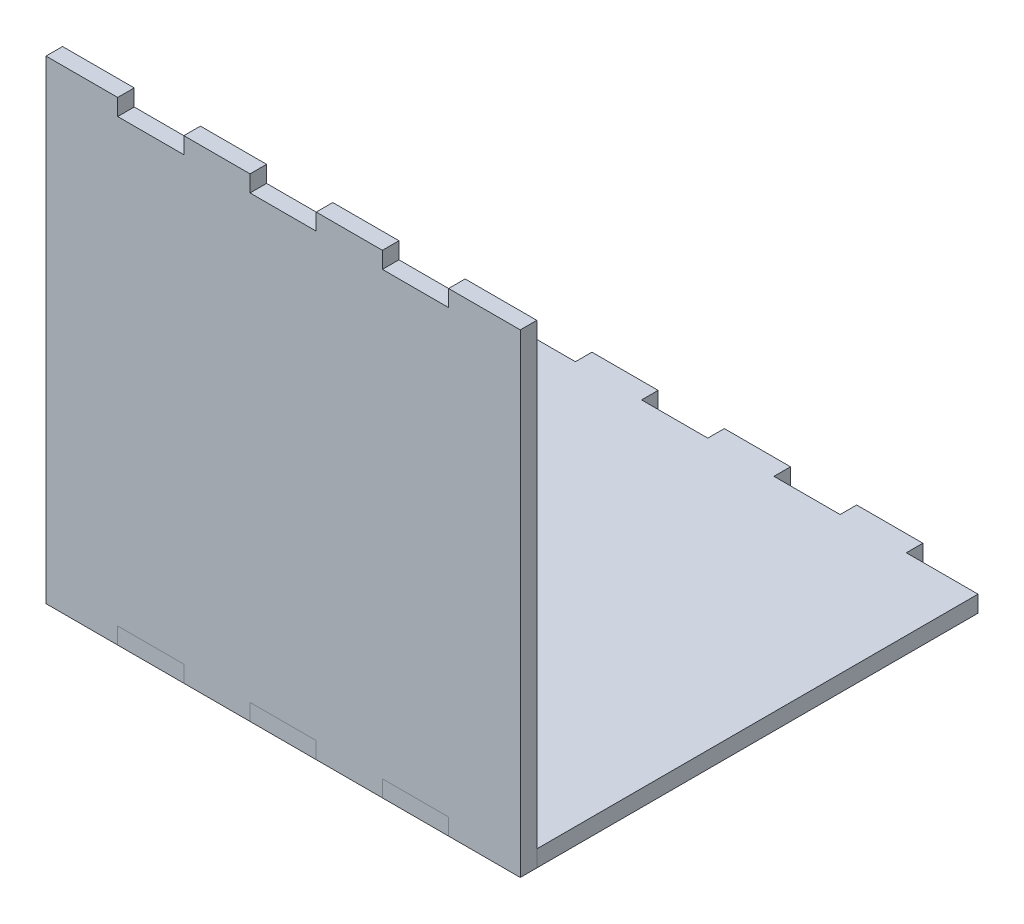
SolidWorks part; units mm, degrees
ref_plane "Alzado" through (0, 0, 0) normal (0, 0, 1) x (1, 0, 0)
ref_plane "Planta" through (0, 0, 0) normal (0, 1, 0) x (1, 0, 0)
ref_plane "Vista lateral" through (0, 0, 0) normal (1, 0, 0) x (0, 0, -1)
sketch "Croquis1" plane through (0, 0, 0) normal (0, 0, 1) x (1, 0, 0)
  line L0 (-3, -3) -> (83, 83) construction
  line L1 (10, 0) -> (22, 0)
  line L2 (0, 0) -> (0, 40) construction
  line L3 (10, 80) -> (22, 80)
  line L4 (80, 0) -> (80, 40) construction
  line L5 (10, 83) -> (10, 80)
  line L6 (-3, -3) -> (-3, 83)
  line L7 (-3, 83) -> (10, 83)
  line L8 (83, -3) -> (83, 83)
  line L9 (-3, -3) -> (10, -3)
  line L10 (-3, 83) -> (83, -3) construction
  line L11 (22, 83) -> (22, 80)
  line L12 (34, 83) -> (34, 80)
  line L13 (46, 83) -> (46, 80)
  line L14 (58, 83) -> (58, 80)
  line L15 (70, 83) -> (70, 80)
  line L16 (10, 83) -> (22, 83) construction
  line L17 (40, 40) -> (111.949, 40) construction
  line L18 (111.949, 40) -> (40, 40) construction
  line L19 (40, 40) -> (-8.8187, 40) construction
  line L20 (70, -3) -> (70, 0)
  line L21 (58, -3) -> (58, 0)
  line L22 (46, -3) -> (46, 0)
  line L23 (22, -3) -> (22, 0)
  line L24 (34, -3) -> (34, 0)
  line L25 (10, -3) -> (10, 0)
  line L26 (22, 83) -> (34, 83)
  line L27 (-3, 83) -> (83, 83) construction
  line L28 (46, 83) -> (58, 83)
  line L29 (70, 83) -> (83, 83)
  line L30 (0, 0) -> (10, 0) construction
  line L31 (0, 0) -> (80, 0) construction
  line L32 (22, 0) -> (34, 0) construction
  line L33 (34, 0) -> (46, 0)
  line L34 (46, 0) -> (58, 0) construction
  line L35 (58, 0) -> (70, 0)
  line L36 (70, 0) -> (80, 0) construction
  line L37 (58, -3) -> (70, -3) construction
  line L38 (70, -3) -> (83, -3)
  line L39 (-3, -3) -> (83, -3) construction
  line L40 (34, -3) -> (46, -3) construction
  line L41 (46, -3) -> (58, -3)
  line L42 (10, -3) -> (22, -3) construction
  line L43 (22, -3) -> (34, -3)
  line L44 (0, 80) -> (10, 80) construction
  line L45 (0, 80) -> (80, 80) construction
  line L46 (22, 80) -> (34, 80) construction
  line L47 (34, 80) -> (46, 80)
  line L48 (46, 80) -> (58, 80) construction
  line L49 (58, 80) -> (70, 80)
  line L50 (70, 80) -> (80, 80) construction
  line L51 (0, 40) -> (0, 80) construction
  line L52 (0, 0) -> (0, 80) construction
  line L53 (80, 40) -> (80, 80) construction
  line L54 (80, 0) -> (80, 80) construction
  point P12 (0, 0)
  point P26 (0, 0)
  dimension "D1" = 80
  dimension "D2" = 80
  dimension "D5" = 12
  dimension "D6" = 10
  dimension "D3" = 3
  dimension "D4" = 6
extrude "Saliente-Extruir1" add sketch "Croquis1" along normal blind 3 contours L14 L49 L15 L29 L8 L38 L20 L35 L21 L41 L22 L33 L24 L43 L23 L1 L25 L9 L6 L7 L5 L3 L11 L26 L12 L47 L13 L28
sketch "Croquis4" plane through (0, 0, 0) normal (0, 1, 0) x (1, 0, 0)
  line L0 (-3, 0) -> (-3, 80)
  line L1 (0, 0) -> (10, 0)
  line L3 (0, 80) -> (10, 80)
  line L4 (80, 0) -> (80, 40) construction
  line L5 (10, 83) -> (22, 83)
  line L6 (83, 0) -> (83, 80)
  line L7 (10, -3) -> (22, -3)
  line L8 (-3, 0) -> (0, 0)
  line L9 (83, 0) -> (80, 0)
  line L10 (0, 80) -> (-3, 80)
  line L11 (80, 80) -> (83, 80)
  line L12 (10, 0) -> (10, -3)
  line L13 (22, 0) -> (22, -3)
  line L14 (34, 0) -> (34, -3)
  line L15 (46, 0) -> (46, -3)
  line L16 (58, 0) -> (58, -3)
  line L17 (70, 0) -> (70, -3)
  line L18 (0, 40) -> (80, 40) construction
  line L19 (70, 80) -> (70, 83)
  line L20 (58, 80) -> (58, 83)
  line L21 (46, 80) -> (46, 83)
  line L22 (34, 80) -> (34, 83)
  line L23 (22, 80) -> (22, 83)
  line L24 (10, 80) -> (10, 83)
  line L26 (-3, -3) -> (-3, 83) construction
  line L28 (-3, 83) -> (83, 83) construction
  line L30 (34, 83) -> (46, 83)
  line L32 (58, 83) -> (70, 83)
  line L35 (83, -3) -> (83, 83) construction
  line L38 (-3, -3) -> (83, -3) construction
  line L40 (58, -3) -> (70, -3)
  line L43 (34, -3) -> (46, -3)
  line L46 (0, 0) -> (0, 80) construction
  line L48 (22, 80) -> (34, 80)
  line L49 (0, 80) -> (80, 80) construction
  line L51 (46, 80) -> (58, 80)
  line L53 (70, 80) -> (80, 80)
  line L55 (70, 0) -> (80, 0)
  line L56 (0, 0) -> (80, 0) construction
  line L58 (46, 0) -> (58, 0)
  line L60 (22, 0) -> (34, 0)
  line L62 (80, 0) -> (80, 80) construction
  dimension "D2" = 80
extrude "Saliente-Extruir4" add sketch "Croquis4" against normal blind 3 separate body
